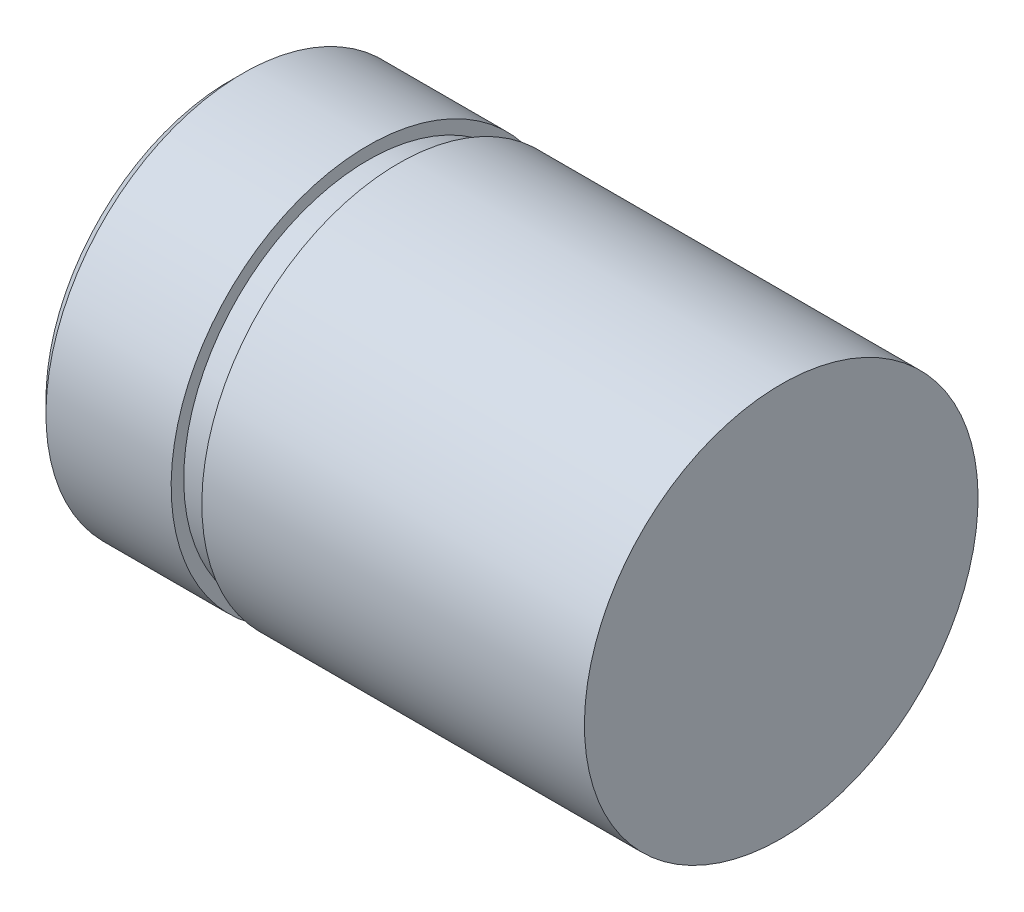
SolidWorks part; units mm, degrees
material "Cast Carbon Steel"
ref_plane "Front" through (0, 0, 0) normal (0, 0, 1) x (1, 0, 0)
ref_plane "Top" through (0, 0, 0) normal (0, 1, 0) x (1, 0, 0)
ref_plane "Right" through (0, 0, 0) normal (1, 0, 0) x (0, 0, -1)
sketch "Sketch1" plane through (0, 0, 0) normal (1, 0, 0) x (0, 0, -1)
  line L0 (0, 0) -> (0, 5.9436) construction
  line L1 (-0.518, 5.921) -> (-0.7571, 8.6537)
  line L2 (0.7571, 8.6537) -> (2.8067, 8.4744)
  line L3 (2.8067, 8.4744) -> (3.7141, 5.8857)
  line L4 (0.518, 5.921) -> (0.7571, 8.6537)
  line L5 (-0.7571, 8.6537) -> (-2.8067, 8.4744)
  line L6 (-2.8067, 8.4744) -> (-3.7141, 5.8857)
  line L7 (-3.7141, 5.8857) -> (-3.1719, 5.0265) construction
  line L8 (3.7141, 5.8857) -> (3.1719, 5.0265) construction
  line L9 (0, -5.9436) -> (0, -7.5946) construction
  line L10 (-2.8067, 8.4744) -> (-0.518, 5.921) construction
  line L11 (0, 5.9436) -> (0, 8.6868) construction
  line L12 (-5.9436, 0) -> (5.9436, 0) construction
  circle A0 centre (0, 0) radius 5.9436 construction
  arc A1 (-0.518, 5.921) -> (0.518, 5.921) centre (0, 0) ccw
  circle A3 centre (0, 0) radius 9.5885 construction
  circle A4 centre (-1.6623, 7.1977) radius 0.5969
  circle A5 centre (1.6623, 7.1977) radius 0.5969
  arc A6 (-3.7141, 5.8857) -> (3.7141, 5.8857) centre (0, -0.3428) ccw
  point P0 (0, -7.5946)
  dimension "A" = 11.8872
  dimension "Hole" = 1.1938
  dimension "Smin" = 1.016
  dimension "H" = 2.7432
  dimension "D2" = 2.0574
  dimension "Angle" = 5
extrude "Extrude1" [suppressed] add sketch "Sketch1" along normal mid plane 0.889
fillet "Fillet1" [suppressed] radius 0.9017
sketch "Sketch2" plane through (0, 0, 0) normal (0, 0, 1) x (1, 0, 0)
  line L0 (-4.9403, 0) -> (12.8397, 0)
  line L1 (12.8397, 0) -> (12.8397, -6.35)
  line L2 (-0.4953, -6.35) -> (-4.5339, -6.35)
  line L3 (12.8397, -6.35) -> (0.4953, -6.35)
  line L4 (0.4953, -6.35) -> (0.4953, -5.9436)
  line L5 (0.4953, -5.9436) -> (-0.4953, -5.9436)
  line L6 (-0.4953, -5.9436) -> (-0.4953, -6.35)
  line L7 (-0.4953, -6.35) -> (-4.9403, -6.35) construction
  line L8 (-4.9403, -6.35) -> (-4.9403, 0) construction
  line L9 (12.8397, 0) -> (76.391, 0) construction
  line L10 (-4.5339, -6.35) -> (-4.9403, -5.9436)
  line L11 (-4.9403, -5.9436) -> (-4.9403, 0)
  point P10 (0, -5.9436)
  dimension "D2" = 17.78
  dimension "D3" = 4.445
  dimension "D1" = 45
revolve "Revolve1" add sketch "Sketch2" angle 360 about L9
delete or keep bodies "Body-Delete1" [suppressed] type delete bodies bodies 122
equation "\"D2@Sketch2\" = \"D1@Extrude1\"*20"
equation "\"D3@Sketch2\" = \"D2@Sketch2\"/4"
equation "\"D2@Sketch1\" = \"H@Sketch1\"*.75"
